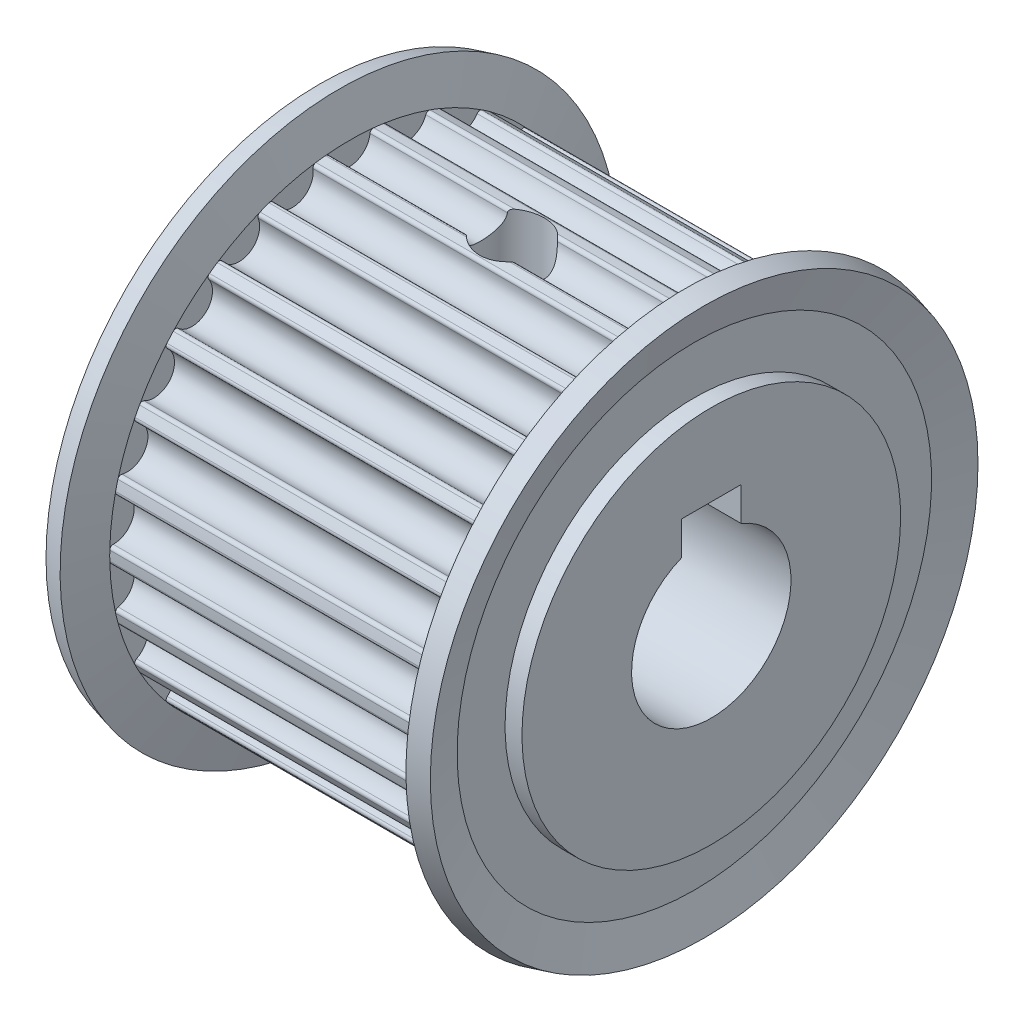
SolidWorks part; units mm, degrees
ref_plane "Front Plane" through (0, 0, 0) normal (0, 0, 1) x (1, 0, 0)
ref_plane "Top Plane" through (0, 0, 0) normal (0, 1, 0) x (1, 0, 0)
ref_plane "Right Plane" through (0, 0, 0) normal (1, 0, 0) x (0, 0, -1)
ref_plane "Plane1" through (0, 0, 0) normal (0, 0, 1) x (1, 0, 0)
sketch "Sketch1" plane through (0, 0, 0) normal (0, 0, 1) x (1, 0, 0)
  line L0 (0, 0) -> (0, 9.5)
  line L1 (0, 9.5) -> (0.85, 9.5)
  line L2 (0.85, 9.5) -> (0.85, 11.9033)
  line L3 (0.85, 11.9033) -> (0.3576, 13.7412)
  line L4 (0.3576, 13.7412) -> (1.3235, 14)
  line L5 (1.3235, 14) -> (1.85, 12.035)
  line L6 (1.85, 12.035) -> (18.15, 12.035)
  line L7 (18.15, 12.035) -> (18.6765, 14)
  line L8 (18.6765, 14) -> (19.6424, 13.7412)
  line L9 (19.6424, 13.7412) -> (19.15, 11.9033)
  line L10 (19.15, 11.9033) -> (19.15, 9.5)
  line L11 (19.15, 9.5) -> (20, 9.5)
  line L12 (20, 9.5) -> (20, 0)
  line L13 (20, 0) -> (0, 0)
  line L14 (20, 0) -> (0, 0) construction
revolve "Revolve1" add sketch "Sketch1" angle 360 about L14
ref_plane "Plane2" through (10, 0, 0) normal (1, 0, 0) x (0, 0, -1)
sketch "Sketch2" plane through (10, 0, 0) normal (1, 0, 0) x (0, 0, -1)
  line L0 (-1.2493, 12.352) -> (-1.2111, 11.9739)
  line L1 (1.2111, 11.9739) -> (1.2493, 12.352)
  arc A0 (-1.2111, 11.9739) -> (-1.0248, 11.8218) centre (-1.194, 11.8048) cw
  arc A1 (-1.0248, 11.8218) -> (1.0248, 11.8218) centre (0, 11.925) ccw
  arc A2 (1.0248, 11.8218) -> (1.2111, 11.9739) centre (1.194, 11.8048) cw
  arc A3 (1.2493, 12.352) -> (-1.2493, 12.352) centre (0, 0) ccw
extrude "Cut-Extrude1" cut sketch "Sketch2" against normal blind 8.15 and the other way blind 8.15
ref_plane "Plane3" through (10, 0, 0) normal (1, 0, 0) x (0, 0, -1)
sketch "Sketch3" plane through (10, 0, 0) normal (1, 0, 0) x (0, 0, -1)
  line L0 (-4.169, 11.6941) -> (-4.0414, 11.3361)
  line L1 (-1.6897, 11.9158) -> (-1.743, 12.292)
  arc A0 (-4.0414, 11.3361) -> (-3.8242, 11.233) centre (-3.9843, 11.176) cw
  arc A1 (-3.8242, 11.233) -> (-1.8341, 11.7235) centre (-2.8538, 11.5785) ccw
  arc A2 (-1.8341, 11.7235) -> (-1.6897, 11.9158) centre (-1.6658, 11.7475) cw
  arc A3 (-1.743, 12.292) -> (-4.169, 11.6941) centre (0, 0) ccw
extrude "Cut-Extrude2" cut sketch "Sketch3" against normal blind 8.15 and the other way blind 8.15
ref_plane "Plane4" through (10, 0, 0) normal (1, 0, 0) x (0, 0, -1)
sketch "Sketch4" plane through (10, 0, 0) normal (1, 0, 0) x (0, 0, -1)
  line L0 (-6.8465, 10.3566) -> (-6.6369, 10.0396)
  line L1 (-4.4922, 11.1652) -> (-4.634, 11.5177)
  arc A0 (-6.6369, 10.0396) -> (-6.4013, 9.9914) centre (-6.5432, 9.8977) cw
  arc A1 (-6.4013, 9.9914) -> (-4.5864, 10.9439) centre (-5.5418, 10.5591) ccw
  arc A2 (-4.5864, 10.9439) -> (-4.4922, 11.1652) centre (-4.4288, 11.0075) cw
  arc A3 (-4.634, 11.5177) -> (-6.8465, 10.3566) centre (0, 0) ccw
extrude "Cut-Extrude3" cut sketch "Sketch4" against normal blind 8.15 and the other way blind 8.15
ref_plane "Plane5" through (10, 0, 0) normal (1, 0, 0) x (0, 0, -1)
sketch "Sketch5" plane through (10, 0, 0) normal (1, 0, 0) x (0, 0, -1)
  line L0 (-9.126, 8.4171) -> (-8.8467, 8.1595)
  line L1 (-7.0337, 9.7657) -> (-7.2558, 10.074)
  arc A0 (-8.8467, 8.1595) -> (-8.6064, 8.1692) centre (-8.7217, 8.0443) cw
  arc A1 (-8.6064, 8.1692) -> (-7.0722, 9.5283) centre (-7.9077, 8.926) ccw
  arc A2 (-7.0722, 9.5283) -> (-7.0337, 9.7657) centre (-6.9343, 9.6277) cw
  arc A3 (-7.2558, 10.074) -> (-9.126, 8.4171) centre (0, 0) ccw
extrude "Cut-Extrude4" cut sketch "Sketch5" against normal blind 8.15 and the other way blind 8.15
ref_plane "Plane6" through (10, 0, 0) normal (1, 0, 0) x (0, 0, -1)
sketch "Sketch6" plane through (10, 0, 0) normal (1, 0, 0) x (0, 0, -1)
  line L0 (-10.8752, 5.9886) -> (-10.5423, 5.8053)
  line L1 (-9.1664, 7.7986) -> (-9.4558, 8.0449)
  arc A0 (-10.5423, 5.8053) -> (-10.3113, 5.8721) centre (-10.3934, 5.7233) cw
  arc A1 (-10.3113, 5.8721) -> (-9.147, 7.559) centre (-9.8141, 6.7742) ccw
  arc A2 (-9.147, 7.559) -> (-9.1664, 7.7986) centre (-9.0369, 7.6885) cw
  arc A3 (-9.4558, 8.0449) -> (-10.8752, 5.9886) centre (0, 0) ccw
extrude "Cut-Extrude5" cut sketch "Sketch6" against normal blind 8.15 and the other way blind 8.15
ref_plane "Plane7" through (10, 0, 0) normal (1, 0, 0) x (0, 0, -1)
sketch "Sketch7" plane through (10, 0, 0) normal (1, 0, 0) x (0, 0, -1)
  line L0 (-11.9923, 3.2119) -> (-11.6253, 3.1136)
  line L1 (-10.7663, 5.3784) -> (-11.1063, 5.5482)
  arc A0 (-11.6253, 3.1136) -> (-11.417, 3.2338) centre (-11.461, 3.0697) cw
  arc A1 (-11.417, 3.2338) -> (-10.6902, 5.1503) centre (-11.1501, 4.2287) ccw
  arc A2 (-10.6902, 5.1503) -> (-10.7663, 5.3784) centre (-10.6143, 5.3024) cw
  arc A3 (-11.1063, 5.5482) -> (-11.9923, 3.2119) centre (0, 0) ccw
extrude "Cut-Extrude6" cut sketch "Sketch7" against normal blind 8.15 and the other way blind 8.15
ref_plane "Plane8" through (10, 0, 0) normal (1, 0, 0) x (0, 0, -1)
sketch "Sketch8" plane through (10, 0, 0) normal (1, 0, 0) x (0, 0, -1)
  line L0 (-12.4125, 0.2487) -> (-12.0326, 0.2411)
  line L1 (-11.7406, 2.6455) -> (-12.1113, 2.7291)
  arc A0 (-12.0326, 0.2411) -> (-11.8591, 0.4076) centre (-11.8626, 0.2377) cw
  arc A1 (-11.8591, 0.4076) -> (-11.6121, 2.4423) centre (-11.8381, 1.4374) ccw
  arc A2 (-11.6121, 2.4423) -> (-11.7406, 2.6455) centre (-11.5748, 2.6082) cw
  arc A3 (-12.1113, 2.7291) -> (-12.4125, 0.2487) centre (0, 0) ccw
extrude "Cut-Extrude7" cut sketch "Sketch8" against normal blind 8.15 and the other way blind 8.15
ref_plane "Plane9" through (10, 0, 0) normal (1, 0, 0) x (0, 0, -1)
sketch "Sketch9" plane through (10, 0, 0) normal (1, 0, 0) x (0, 0, -1)
  line L0 (-12.1113, -2.7291) -> (-11.7406, -2.6455)
  line L1 (-12.0326, -0.2411) -> (-12.4125, -0.2487)
  arc A0 (-11.7406, -2.6455) -> (-11.6121, -2.4423) centre (-11.5748, -2.6082) cw
  arc A1 (-11.6121, -2.4423) -> (-11.8591, -0.4076) centre (-11.8381, -1.4374) ccw
  arc A2 (-11.8591, -0.4076) -> (-12.0326, -0.2411) centre (-11.8626, -0.2377) cw
  arc A3 (-12.4125, -0.2487) -> (-12.1113, -2.7291) centre (0, 0) ccw
extrude "Cut-Extrude8" cut sketch "Sketch9" against normal blind 8.15 and the other way blind 8.15
ref_plane "Plane10" through (10, 0, 0) normal (1, 0, 0) x (0, 0, -1)
sketch "Sketch10" plane through (10, 0, 0) normal (1, 0, 0) x (0, 0, -1)
  line L0 (-11.1063, -5.5482) -> (-10.7663, -5.3784)
  line L1 (-11.6253, -3.1136) -> (-11.9923, -3.2119)
  arc A0 (-10.7663, -5.3784) -> (-10.6902, -5.1503) centre (-10.6143, -5.3024) cw
  arc A1 (-10.6902, -5.1503) -> (-11.417, -3.2338) centre (-11.1501, -4.2287) ccw
  arc A2 (-11.417, -3.2338) -> (-11.6253, -3.1136) centre (-11.461, -3.0697) cw
  arc A3 (-11.9923, -3.2119) -> (-11.1063, -5.5482) centre (0, 0) ccw
extrude "Cut-Extrude9" cut sketch "Sketch10" against normal blind 8.15 and the other way blind 8.15
ref_plane "Plane11" through (10, 0, 0) normal (1, 0, 0) x (0, 0, -1)
sketch "Sketch11" plane through (10, 0, 0) normal (1, 0, 0) x (0, 0, -1)
  line L0 (-9.4558, -8.0449) -> (-9.1664, -7.7986)
  line L1 (-10.5423, -5.8053) -> (-10.8752, -5.9886)
  arc A0 (-9.1664, -7.7986) -> (-9.147, -7.559) centre (-9.0369, -7.6885) cw
  arc A1 (-9.147, -7.559) -> (-10.3113, -5.8721) centre (-9.8141, -6.7742) ccw
  arc A2 (-10.3113, -5.8721) -> (-10.5423, -5.8053) centre (-10.3934, -5.7233) cw
  arc A3 (-10.8752, -5.9886) -> (-9.4558, -8.0449) centre (0, 0) ccw
extrude "Cut-Extrude10" cut sketch "Sketch11" against normal blind 8.15 and the other way blind 8.15
ref_plane "Plane12" through (10, 0, 0) normal (1, 0, 0) x (0, 0, -1)
sketch "Sketch12" plane through (10, 0, 0) normal (1, 0, 0) x (0, 0, -1)
  line L0 (-7.2558, -10.074) -> (-7.0337, -9.7657)
  line L1 (-8.8467, -8.1595) -> (-9.126, -8.4171)
  arc A0 (-7.0337, -9.7657) -> (-7.0722, -9.5283) centre (-6.9343, -9.6277) cw
  arc A1 (-7.0722, -9.5283) -> (-8.6064, -8.1692) centre (-7.9077, -8.926) ccw
  arc A2 (-8.6064, -8.1692) -> (-8.8467, -8.1595) centre (-8.7217, -8.0443) cw
  arc A3 (-9.126, -8.4171) -> (-7.2558, -10.074) centre (0, 0) ccw
extrude "Cut-Extrude11" cut sketch "Sketch12" against normal blind 8.15 and the other way blind 8.15
ref_plane "Plane13" through (10, 0, 0) normal (1, 0, 0) x (0, 0, -1)
sketch "Sketch13" plane through (10, 0, 0) normal (1, 0, 0) x (0, 0, -1)
  line L0 (-4.634, -11.5177) -> (-4.4922, -11.1652)
  line L1 (-6.6369, -10.0396) -> (-6.8465, -10.3566)
  arc A0 (-4.4922, -11.1652) -> (-4.5864, -10.9439) centre (-4.4288, -11.0075) cw
  arc A1 (-4.5864, -10.9439) -> (-6.4013, -9.9914) centre (-5.5418, -10.5591) ccw
  arc A2 (-6.4013, -9.9914) -> (-6.6369, -10.0396) centre (-6.5432, -9.8977) cw
  arc A3 (-6.8465, -10.3566) -> (-4.634, -11.5177) centre (0, 0) ccw
extrude "Cut-Extrude12" cut sketch "Sketch13" against normal blind 8.15 and the other way blind 8.15
ref_plane "Plane14" through (10, 0, 0) normal (1, 0, 0) x (0, 0, -1)
sketch "Sketch14" plane through (10, 0, 0) normal (1, 0, 0) x (0, 0, -1)
  line L0 (-1.743, -12.292) -> (-1.6897, -11.9158)
  line L1 (-4.0414, -11.3361) -> (-4.169, -11.6941)
  arc A0 (-1.6897, -11.9158) -> (-1.8341, -11.7235) centre (-1.6658, -11.7475) cw
  arc A1 (-1.8341, -11.7235) -> (-3.8242, -11.233) centre (-2.8538, -11.5785) ccw
  arc A2 (-3.8242, -11.233) -> (-4.0414, -11.3361) centre (-3.9843, -11.176) cw
  arc A3 (-4.169, -11.6941) -> (-1.743, -12.292) centre (0, 0) ccw
extrude "Cut-Extrude13" cut sketch "Sketch14" against normal blind 8.15 and the other way blind 8.15
ref_plane "Plane15" through (10, 0, 0) normal (1, 0, 0) x (0, 0, -1)
sketch "Sketch15" plane through (10, 0, 0) normal (1, 0, 0) x (0, 0, -1)
  line L0 (1.2493, -12.352) -> (1.2111, -11.9739)
  line L1 (-1.2111, -11.9739) -> (-1.2493, -12.352)
  arc A0 (1.2111, -11.9739) -> (1.0248, -11.8218) centre (1.194, -11.8048) cw
  arc A1 (1.0248, -11.8218) -> (-1.0248, -11.8218) centre (0, -11.925) ccw
  arc A2 (-1.0248, -11.8218) -> (-1.2111, -11.9739) centre (-1.194, -11.8048) cw
  arc A3 (-1.2493, -12.352) -> (1.2493, -12.352) centre (0, 0) ccw
extrude "Cut-Extrude14" cut sketch "Sketch15" against normal blind 8.15 and the other way blind 8.15
ref_plane "Plane16" through (10, 0, 0) normal (1, 0, 0) x (0, 0, -1)
sketch "Sketch16" plane through (10, 0, 0) normal (1, 0, 0) x (0, 0, -1)
  line L0 (4.169, -11.6941) -> (4.0414, -11.3361)
  line L1 (1.6897, -11.9158) -> (1.743, -12.292)
  arc A0 (4.0414, -11.3361) -> (3.8242, -11.233) centre (3.9843, -11.176) cw
  arc A1 (3.8242, -11.233) -> (1.8341, -11.7235) centre (2.8538, -11.5785) ccw
  arc A2 (1.8341, -11.7235) -> (1.6897, -11.9158) centre (1.6658, -11.7475) cw
  arc A3 (1.743, -12.292) -> (4.169, -11.6941) centre (0, 0) ccw
extrude "Cut-Extrude15" cut sketch "Sketch16" against normal blind 8.15 and the other way blind 8.15
ref_plane "Plane17" through (10, 0, 0) normal (1, 0, 0) x (0, 0, -1)
sketch "Sketch17" plane through (10, 0, 0) normal (1, 0, 0) x (0, 0, -1)
  line L0 (6.8465, -10.3566) -> (6.6369, -10.0396)
  line L1 (4.4922, -11.1652) -> (4.634, -11.5177)
  arc A0 (6.6369, -10.0396) -> (6.4013, -9.9914) centre (6.5432, -9.8977) cw
  arc A1 (6.4013, -9.9914) -> (4.5864, -10.9439) centre (5.5418, -10.5591) ccw
  arc A2 (4.5864, -10.9439) -> (4.4922, -11.1652) centre (4.4288, -11.0075) cw
  arc A3 (4.634, -11.5177) -> (6.8465, -10.3566) centre (0, 0) ccw
extrude "Cut-Extrude16" cut sketch "Sketch17" against normal blind 8.15 and the other way blind 8.15
ref_plane "Plane18" through (10, 0, 0) normal (1, 0, 0) x (0, 0, -1)
sketch "Sketch18" plane through (10, 0, 0) normal (1, 0, 0) x (0, 0, -1)
  line L0 (9.126, -8.4171) -> (8.8467, -8.1595)
  line L1 (7.0337, -9.7657) -> (7.2558, -10.074)
  arc A0 (8.8467, -8.1595) -> (8.6064, -8.1692) centre (8.7217, -8.0443) cw
  arc A1 (8.6064, -8.1692) -> (7.0722, -9.5283) centre (7.9077, -8.926) ccw
  arc A2 (7.0722, -9.5283) -> (7.0337, -9.7657) centre (6.9343, -9.6277) cw
  arc A3 (7.2558, -10.074) -> (9.126, -8.4171) centre (0, 0) ccw
extrude "Cut-Extrude17" cut sketch "Sketch18" against normal blind 8.15 and the other way blind 8.15
ref_plane "Plane19" through (10, 0, 0) normal (1, 0, 0) x (0, 0, -1)
sketch "Sketch19" plane through (10, 0, 0) normal (1, 0, 0) x (0, 0, -1)
  line L0 (10.8752, -5.9886) -> (10.5423, -5.8053)
  line L1 (9.1664, -7.7986) -> (9.4558, -8.0449)
  arc A0 (10.5423, -5.8053) -> (10.3113, -5.8721) centre (10.3934, -5.7233) cw
  arc A1 (10.3113, -5.8721) -> (9.147, -7.559) centre (9.8141, -6.7742) ccw
  arc A2 (9.147, -7.559) -> (9.1664, -7.7986) centre (9.0369, -7.6885) cw
  arc A3 (9.4558, -8.0449) -> (10.8752, -5.9886) centre (0, 0) ccw
extrude "Cut-Extrude18" cut sketch "Sketch19" against normal blind 8.15 and the other way blind 8.15
ref_plane "Plane20" through (10, 0, 0) normal (1, 0, 0) x (0, 0, -1)
sketch "Sketch20" plane through (10, 0, 0) normal (1, 0, 0) x (0, 0, -1)
  line L0 (11.9923, -3.2119) -> (11.6253, -3.1136)
  line L1 (10.7663, -5.3784) -> (11.1063, -5.5482)
  arc A0 (11.6253, -3.1136) -> (11.417, -3.2338) centre (11.461, -3.0697) cw
  arc A1 (11.417, -3.2338) -> (10.6902, -5.1503) centre (11.1501, -4.2287) ccw
  arc A2 (10.6902, -5.1503) -> (10.7663, -5.3784) centre (10.6143, -5.3024) cw
  arc A3 (11.1063, -5.5482) -> (11.9923, -3.2119) centre (0, 0) ccw
extrude "Cut-Extrude19" cut sketch "Sketch20" against normal blind 8.15 and the other way blind 8.15
ref_plane "Plane21" through (10, 0, 0) normal (1, 0, 0) x (0, 0, -1)
sketch "Sketch21" plane through (10, 0, 0) normal (1, 0, 0) x (0, 0, -1)
  line L0 (12.4125, -0.2487) -> (12.0326, -0.2411)
  line L1 (11.7406, -2.6455) -> (12.1113, -2.7291)
  arc A0 (12.0326, -0.2411) -> (11.8591, -0.4076) centre (11.8626, -0.2377) cw
  arc A1 (11.8591, -0.4076) -> (11.6121, -2.4423) centre (11.8381, -1.4374) ccw
  arc A2 (11.6121, -2.4423) -> (11.7406, -2.6455) centre (11.5748, -2.6082) cw
  arc A3 (12.1113, -2.7291) -> (12.4125, -0.2487) centre (0, 0) ccw
extrude "Cut-Extrude20" cut sketch "Sketch21" against normal blind 8.15 and the other way blind 8.15
ref_plane "Plane22" through (10, 0, 0) normal (1, 0, 0) x (0, 0, -1)
sketch "Sketch22" plane through (10, 0, 0) normal (1, 0, 0) x (0, 0, -1)
  line L0 (12.1113, 2.7291) -> (11.7406, 2.6455)
  line L1 (12.0326, 0.2411) -> (12.4125, 0.2487)
  arc A0 (11.7406, 2.6455) -> (11.6121, 2.4423) centre (11.5748, 2.6082) cw
  arc A1 (11.6121, 2.4423) -> (11.8591, 0.4076) centre (11.8381, 1.4374) ccw
  arc A2 (11.8591, 0.4076) -> (12.0326, 0.2411) centre (11.8626, 0.2377) cw
  arc A3 (12.4125, 0.2487) -> (12.1113, 2.7291) centre (0, 0) ccw
extrude "Cut-Extrude21" cut sketch "Sketch22" against normal blind 8.15 and the other way blind 8.15
ref_plane "Plane23" through (10, 0, 0) normal (1, 0, 0) x (0, 0, -1)
sketch "Sketch23" plane through (10, 0, 0) normal (1, 0, 0) x (0, 0, -1)
  line L0 (11.1063, 5.5482) -> (10.7663, 5.3784)
  line L1 (11.6253, 3.1136) -> (11.9923, 3.2119)
  arc A0 (10.7663, 5.3784) -> (10.6902, 5.1503) centre (10.6143, 5.3024) cw
  arc A1 (10.6902, 5.1503) -> (11.417, 3.2338) centre (11.1501, 4.2287) ccw
  arc A2 (11.417, 3.2338) -> (11.6253, 3.1136) centre (11.461, 3.0697) cw
  arc A3 (11.9923, 3.2119) -> (11.1063, 5.5482) centre (0, 0) ccw
extrude "Cut-Extrude22" cut sketch "Sketch23" against normal blind 8.15 and the other way blind 8.15
ref_plane "Plane24" through (10, 0, 0) normal (1, 0, 0) x (0, 0, -1)
sketch "Sketch24" plane through (10, 0, 0) normal (1, 0, 0) x (0, 0, -1)
  line L0 (9.4558, 8.0449) -> (9.1664, 7.7986)
  line L1 (10.5423, 5.8053) -> (10.8752, 5.9886)
  arc A0 (9.1664, 7.7986) -> (9.147, 7.559) centre (9.0369, 7.6885) cw
  arc A1 (9.147, 7.559) -> (10.3113, 5.8721) centre (9.8141, 6.7742) ccw
  arc A2 (10.3113, 5.8721) -> (10.5423, 5.8053) centre (10.3934, 5.7233) cw
  arc A3 (10.8752, 5.9886) -> (9.4558, 8.0449) centre (0, 0) ccw
extrude "Cut-Extrude23" cut sketch "Sketch24" against normal blind 8.15 and the other way blind 8.15
ref_plane "Plane25" through (10, 0, 0) normal (1, 0, 0) x (0, 0, -1)
sketch "Sketch25" plane through (10, 0, 0) normal (1, 0, 0) x (0, 0, -1)
  line L0 (7.2558, 10.074) -> (7.0337, 9.7657)
  line L1 (8.8467, 8.1595) -> (9.126, 8.4171)
  arc A0 (7.0337, 9.7657) -> (7.0722, 9.5283) centre (6.9343, 9.6277) cw
  arc A1 (7.0722, 9.5283) -> (8.6064, 8.1692) centre (7.9077, 8.926) ccw
  arc A2 (8.6064, 8.1692) -> (8.8467, 8.1595) centre (8.7217, 8.0443) cw
  arc A3 (9.126, 8.4171) -> (7.2558, 10.074) centre (0, 0) ccw
extrude "Cut-Extrude24" cut sketch "Sketch25" against normal blind 8.15 and the other way blind 8.15
ref_plane "Plane26" through (10, 0, 0) normal (1, 0, 0) x (0, 0, -1)
sketch "Sketch26" plane through (10, 0, 0) normal (1, 0, 0) x (0, 0, -1)
  line L0 (4.634, 11.5177) -> (4.4922, 11.1652)
  line L1 (6.6369, 10.0396) -> (6.8465, 10.3566)
  arc A0 (4.4922, 11.1652) -> (4.5864, 10.9439) centre (4.4288, 11.0075) cw
  arc A1 (4.5864, 10.9439) -> (6.4013, 9.9914) centre (5.5418, 10.5591) ccw
  arc A2 (6.4013, 9.9914) -> (6.6369, 10.0396) centre (6.5432, 9.8977) cw
  arc A3 (6.8465, 10.3566) -> (4.634, 11.5177) centre (0, 0) ccw
extrude "Cut-Extrude25" cut sketch "Sketch26" against normal blind 8.15 and the other way blind 8.15
ref_plane "Plane27" through (10, 0, 0) normal (1, 0, 0) x (0, 0, -1)
sketch "Sketch27" plane through (10, 0, 0) normal (1, 0, 0) x (0, 0, -1)
  line L0 (1.743, 12.292) -> (1.6897, 11.9158)
  line L1 (4.0414, 11.3361) -> (4.169, 11.6941)
  arc A0 (1.6897, 11.9158) -> (1.8341, 11.7235) centre (1.6658, 11.7475) cw
  arc A1 (1.8341, 11.7235) -> (3.8242, 11.233) centre (2.8538, 11.5785) ccw
  arc A2 (3.8242, 11.233) -> (4.0414, 11.3361) centre (3.9843, 11.176) cw
  arc A3 (4.169, 11.6941) -> (1.743, 12.292) centre (0, 0) ccw
extrude "Cut-Extrude26" cut sketch "Sketch27" against normal blind 8.15 and the other way blind 8.15
ref_plane "Plane28" through (0, 0, 0) normal (0, 0, 1) x (1, 0, 0)
sketch "Sketch28" plane through (0, 0, 0) normal (0, 0, 1) x (1, 0, 0)
  line L0 (0, 0) -> (0, 4)
  line L1 (0, 4) -> (20, 4)
  line L2 (20, 4) -> (20, 0)
  line L3 (20, 0) -> (0, 0)
  line L4 (20, 0) -> (0, 0) construction
revolve "Cut-Revolve1" cut sketch "Sketch28" angle 360 about L4
ref_plane "Plane29" through (10, 0, 0) normal (1, 0, 0) x (0, 0, -1)
sketch "Sketch29" plane through (10, 0, 0) normal (1, 0, 0) x (0, 0, -1)
  line L0 (0, 12.035) -> (1.621, 12.035)
  line L1 (1.621, 12.035) -> (1.621, 0)
  line L2 (1.621, 0) -> (0, 0)
  line L3 (0, 0) -> (0, 12.035)
  line L4 (0, 0) -> (0, 12.035) construction
revolve "Cut-Revolve2" cut sketch "Sketch29" angle 360 about L4
ref_plane "Plane30" through (10, 0, 0) normal (1, 0, 0) x (0, 0, -1)
sketch "Sketch30" plane through (10, 0, 0) normal (1, 0, 0) x (0, 0, -1)
  line L0 (9.9046, -6.8367) -> (8.9838, -8.1707)
  line L1 (8.9838, -8.1707) -> (-0.9208, -1.3341)
  line L2 (-0.9208, -1.3341) -> (0, 0)
  line L3 (0, 0) -> (9.9046, -6.8367)
  line L4 (0, 0) -> (9.9046, -6.8367) construction
revolve "Cut-Revolve3" cut sketch "Sketch30" angle 360 about L4
ref_plane "Plane31" through (0, 0, 0) normal (1, 0, 0) x (0, 0, -1)
sketch "Sketch31" plane through (0, 0, 0) normal (1, 0, 0) x (0, 0, -1)
  line L0 (-1.5, 0) -> (1.5, 0)
  line L1 (1.5, 0) -> (1.5, 5.4)
  line L2 (1.5, 5.4) -> (-1.5, 5.4)
  line L3 (-1.5, 5.4) -> (-1.5, 0)
extrude "Cut-Extrude27" cut sketch "Sketch31" along normal blind 20
